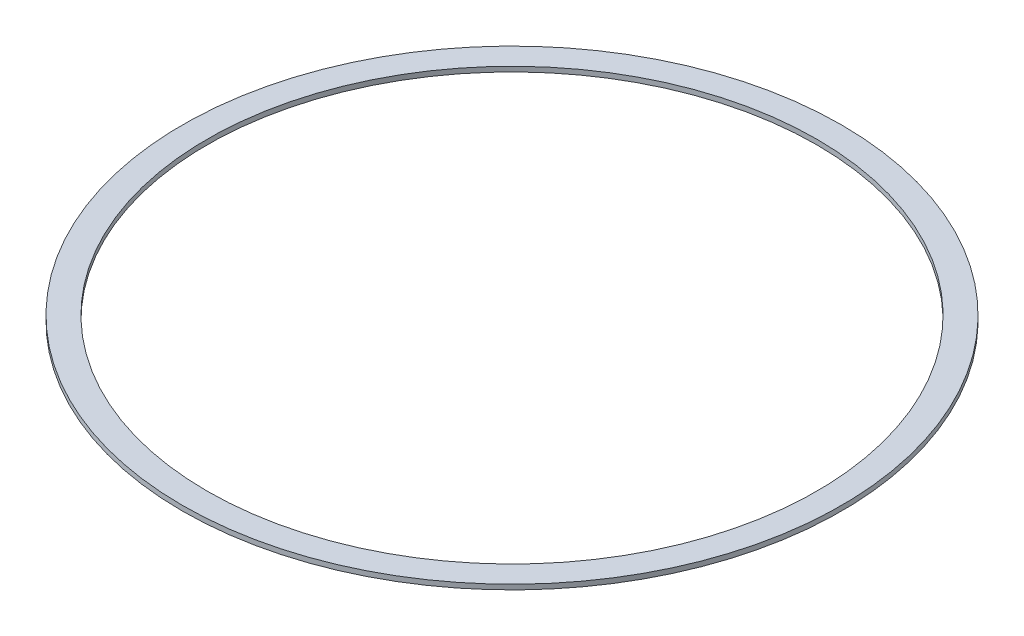
SolidWorks part; units mm, degrees
ref_plane "Front Plane" through (0, 0, 0) normal (0, 0, 1) x (1, 0, 0)
ref_plane "Top Plane" through (0, 0, 0) normal (0, 1, 0) x (1, 0, 0)
ref_plane "Right Plane" through (0, 0, 0) normal (1, 0, 0) x (0, 0, -1)
sketch "Sketch1" plane through (0, 0, 0) normal (0, 1, 0) x (1, 0, 0)
  line L0 (185, 0) -> (-185, 0) construction
  circle A0 centre (0, 0) radius 185
  circle A1 centre (0, 0) radius 200
  dimension "D1" = 370
  dimension "D2" = 400
extrude "Boss-Extrude1" add sketch "Sketch1" along normal mid plane 3
